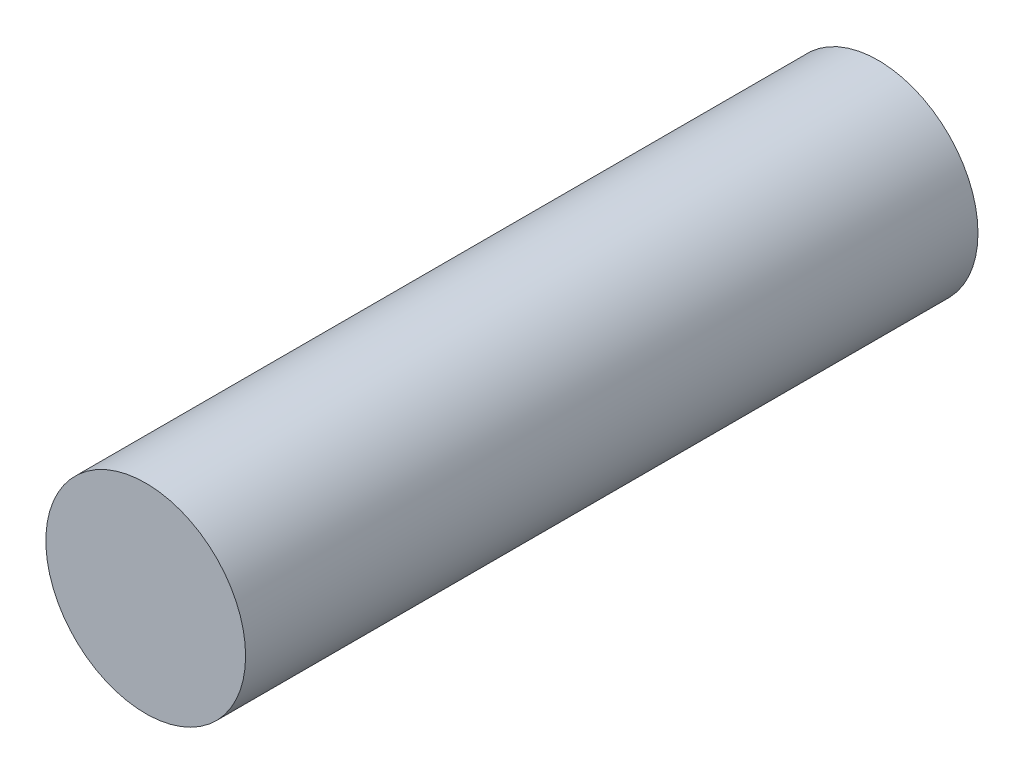
SolidWorks part; units mm, degrees
ref_plane "Ön Düzlem" through (0, 0, 0) normal (0, 0, 1) x (1, 0, 0)
ref_plane "Üst Düzlem" through (0, 0, 0) normal (0, 1, 0) x (1, 0, 0)
ref_plane "Sağ Düzlem" through (0, 0, 0) normal (1, 0, 0) x (0, 0, -1)
sketch "Çizim1" plane through (0, 0, 0) normal (0, 0, 1) x (1, 0, 0)
  circle A0 centre (0, 0) radius 9
  dimension "D1" = 18
extrude "Yükseklik-Ekstrüzyon1" add sketch "Çizim1" along normal blind 66
